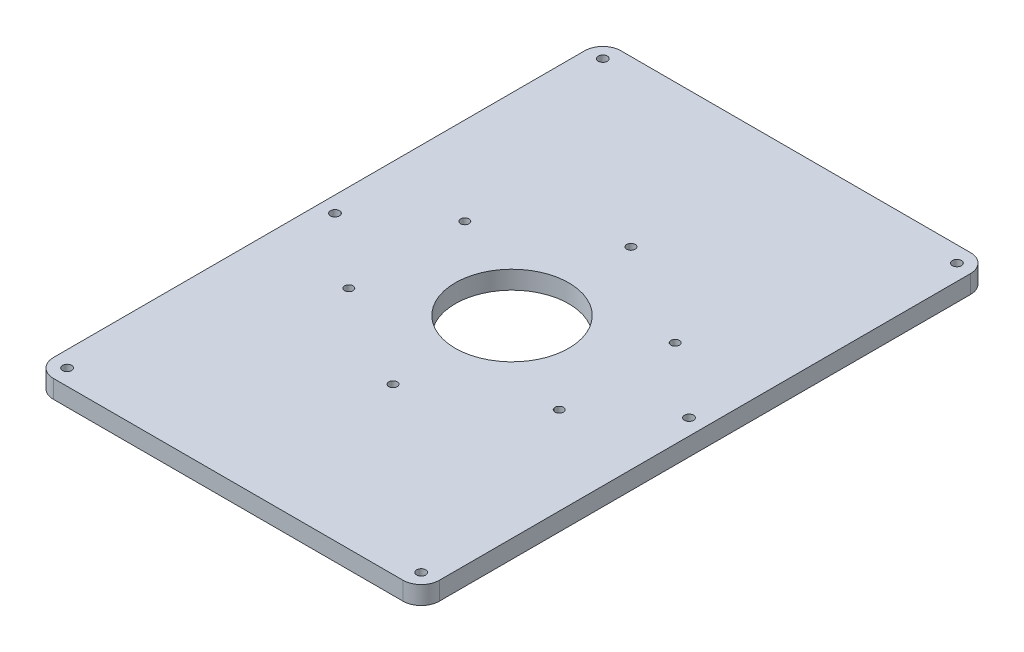
SolidWorks part; units mm, degrees
ref_plane "Front Plane" through (0, 0, 0) normal (0, 0, 1) x (1, 0, 0)
ref_plane "Top Plane" through (0, 0, 0) normal (0, 1, 0) x (1, 0, 0)
ref_plane "Right Plane" through (0, 0, 0) normal (1, 0, 0) x (0, 0, -1)
sketch "Sketch1" plane through (0, 0, 0) normal (0, 1, 0) x (1, 0, 0)
  line L1 (-85, 125) -> (85, 125)
  line L2 (-85, 125) -> (-85, -125)
  line L3 (-85, -125) -> (85, -125)
  line L4 (85, 125) -> (85, -125)
  line L5 (-85, 125) -> (85, -125) construction
  line L6 (-85, -125) -> (85, 125) construction
  point P0 (0, 0)
  dimension "D1" = 250
  dimension "D2" = 170
extrude "Boss-Extrude1" add sketch "Sketch1" along normal blind 8
sketch "Sketch3" plane through (0, 8, 0) normal (0, 1, 0) x (1, 0, 0)
  line L8 (-60.1498, 0) -> (60.1498, 0) construction
  line L9 (0, -57.7777) -> (0, 57.7777) construction
  line L22 (85, 125) -> (-85, 125) construction
  line L23 (-85, 125) -> (-85, -125) construction
  line L24 (-85, 125) -> (-85, -125) construction
  circle A0 centre (-78, 118) radius 2
  circle A1 centre (78, 118) radius 2
  circle A2 centre (78, -118) radius 2
  circle A3 centre (-78, -118) radius 2
  circle A4 centre (-78, 0) radius 2
  circle A5 centre (78, 0) radius 2
  point P13 (0, 0)
  point P17 (0, 0)
  dimension "D4" = 7
  dimension "D6" = 7
  dimension "D5" = 7
extrude "Cut-Extrude2" cut sketch "Sketch3" against normal blind 8
fillet "Fillet1" radius 8 4 edges at (85, 4, 125) (-85, 4, 125) (85, 4, -125) (-85, 4, -125)
sketch "Croquis1" plane through (0, 8, 0) normal (0, 1, 0) x (1, 0, 0)
  circle A0 centre (0, 0) radius 25
  circle A9 centre (0, 52.4128) radius 1.866
  circle A10 centre (-46.3437, 25.5406) radius 1.866
  circle A11 centre (0, -52.4128) radius 1.866
  circle A12 centre (-46.3437, -25.5406) radius 1.866
  circle A13 centre (46.3437, 25.5406) radius 1.866
  circle A14 centre (46.3437, -25.5406) radius 1.866
  dimension "D1" = 50
extrude "Cortar-Extruir3" cut sketch "Croquis1" against normal blind 10
